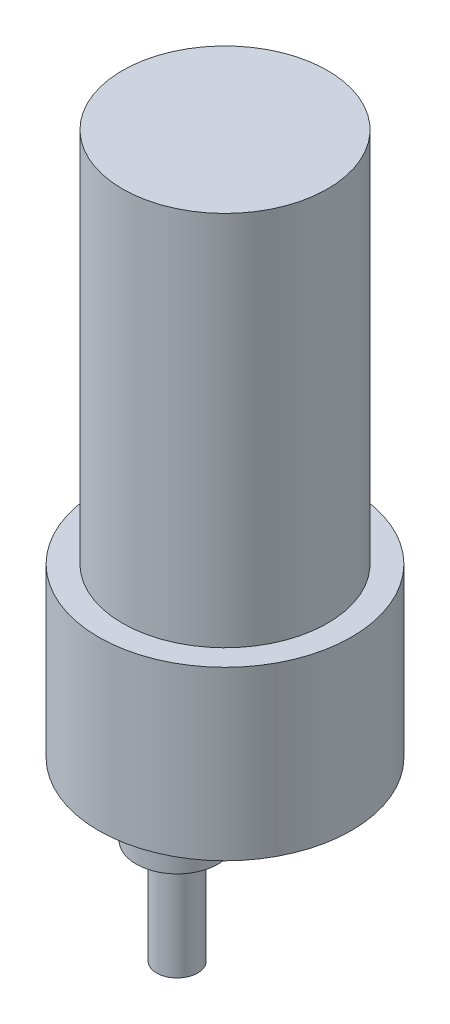
SolidWorks part; units mm, degrees
ref_plane "Plan de face" through (0, 0, 0) normal (0, 0, 1) x (1, 0, 0)
ref_plane "Plan de dessus" through (0, 0, 0) normal (0, 1, 0) x (1, 0, 0)
ref_plane "Plan de droite" through (0, 0, 0) normal (1, 0, 0) x (0, 0, -1)
sketch "Esquisse1" plane through (0, 0, 0) normal (0, 1, 0) x (1, 0, 0)
  circle A0 centre (0, 0) radius 18.5
  dimension "D1" = 37
extrude "Boss.-Extru.1" add sketch "Esquisse1" along normal blind 24.5
sketch "Esquisse2" plane through (0, 24.5, 0) normal (0, 1, 0) x (1, 0, 0)
  circle A0 centre (0, 0) radius 15
  dimension "D1" = 30
extrude "Boss.-Extru.2" add sketch "Esquisse2" along normal blind 55
sketch "Esquisse3" plane through (0, 0, 0) normal (0, 1, 0) x (1, 0, 0)
  line L0 (0, -7) -> (0, 0) construction
  circle A0 centre (0, -7) radius 6
  dimension "D1" = 12
  dimension "D2" = 7
extrude "Boss.-Extru.3" add sketch "Esquisse3" against normal blind 7
sketch "Esquisse4" plane through (0, -7, 0) normal (0, -1, 0) x (1, 0, 0)
  circle A0 centre (0, 7) radius 3
  dimension "D1" = 6
extrude "Boss.-Extru.4" add sketch "Esquisse4" along normal blind 15.3
sketch "Esquisse5" plane through (0, -22.3, 0) normal (0, -1, 0) x (1, 0, 0)
  line L0 (-1.7313, 4.55) -> (1.7313, 4.55)
  circle A0 centre (0, 7) radius 3 construction
  arc A1 (-1.7313, 4.55) -> (1.7313, 4.55) centre (0, 7) ccw
  dimension "D1" = 2.45
extrude "Enlèv. mat.-Extru.1" cut sketch "Esquisse5" against normal blind 12
hole_wizard "Trou taraudé M31" positions "Esquisse6" profile "Esquisse7" tap size "M3" standard "ISO"
sketch "Esquisse6" plane through (0, 0, 0) normal (0, -1, 0) x (-1, 0, 0)
  line L0 (0, 0) -> (-15.5, 0) construction
  point P0 (-15.5, 0)
  dimension "D1" = 15.5
sketch "Esquisse7" plane through (15.5, 0, 0) normal (1, 0, 0) x (0, 0, -1)
  line L0 (0, 0) -> (0, 5.7511)
  line L1 (0, 5.7511) -> (1.25, 5)
  line L2 (1.25, 5) -> (1.25, 0)
  line L5 (1.25, 0) -> (0, 0)
  line L10 (0, 5.7511) -> (-1.25, 5) construction
  line L11 (0, -6.35) -> (0, 107.95) construction
  dimension "Diamètre du trou pour taraudage" = 2.5
  dimension "Profondeur du trou pour taraudage" = 5
  dimension "Angle de pointe" = 118
cosmetic thread "Filetage de perçage1" parameters "D1"=6, "D2"=3
pattern_circular "Répétition circulaire1" count 6 over 360 about axis through (0, 0, 0) along (0, 1, 0) of "Trou taraudé M31"
cosmetic thread "Filetage de perçage2" parameters "D1"=6, "D2"=3
cosmetic thread "Filetage de perçage3" parameters "D1"=6, "D2"=3
cosmetic thread "Filetage de perçage4" parameters "D1"=6, "D2"=3
cosmetic thread "Filetage de perçage5" parameters "D1"=6, "D2"=3
cosmetic thread "Filetage de perçage6" parameters "D1"=6, "D2"=3
